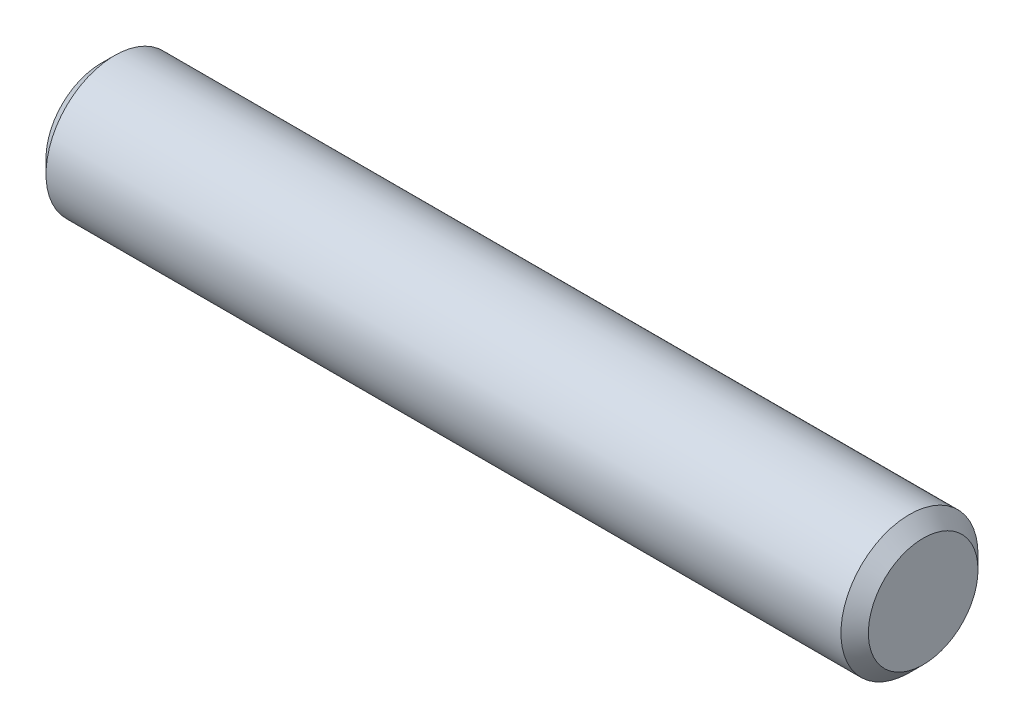
SolidWorks part; units mm, degrees
ref_plane "Front Plane" through (0, 0, 0) normal (0, 0, 1) x (1, 0, 0)
ref_plane "Top Plane" through (0, 0, 0) normal (0, 1, 0) x (1, 0, 0)
ref_plane "Right Plane" through (0, 0, 0) normal (1, 0, 0) x (0, 0, -1)
sketch "Sketch1" plane through (0, 0, 0) normal (0, 0, 1) x (1, 0, 0)
  line L0 (-19.05, 0) -> (19.05, 0) construction
  line L1 (-19.05, 3.175) -> (-19.05, -3.175) construction
  line L2 (19.05, 3.175) -> (19.05, -3.175) construction
  dimension "Diameter" = 6.35
  dimension "Length" = 38.1
sketch "Sketch2" plane through (0, 0, 0) normal (1, 0, 0) x (0, 0, -1)
  circle A0 centre (0, 0) radius 3.175
extrude "Extrude1" add sketch "Sketch2" against normal up to vertex (19.05 mm away) and the other way up to vertex (19.05 mm away) up to point (-19.05, 0, 0) other way up to point (19.05, 0, 0)
chamfer "Chamfer1" distance 0.635 angle 45 2 edges at (19.05, 0, -3.175) (-19.05, 0, -3.175)
equation "\"D1@Chamfer1\" = \"Diameter@Sketch1\"*.1"
